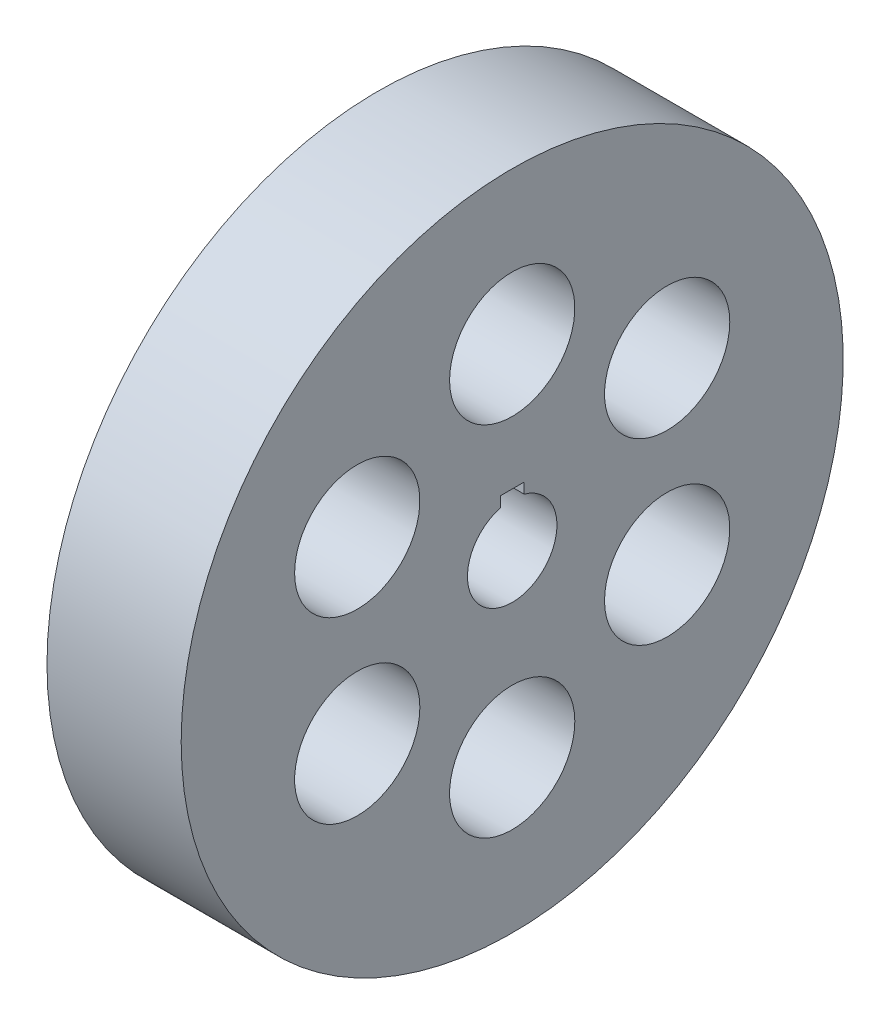
SolidWorks part; units mm, degrees
ref_plane "Front Plane" through (0, 0, 0) normal (0, 0, 1) x (1, 0, 0)
ref_plane "Top Plane" through (0, 0, 0) normal (0, 1, 0) x (1, 0, 0)
ref_plane "Right Plane" through (0, 0, 0) normal (1, 0, 0) x (0, 0, -1)
sketch "Sketch1" plane through (0, 0, 0) normal (0, 1, 0) x (1, 0, 0)
  line L0 (-137.76, 0) -> (199.68, 0) construction
  line L1 (0, 0) -> (0, 30)
  line L2 (0, 30) -> (35, 30)
  line L3 (35, 30) -> (35, 91)
  line L4 (30, 96) -> (25, 96)
  line L5 (25, 96) -> (25, 111)
  line L6 (25, 111) -> (70, 111)
  line L7 (70, 111) -> (70, 0)
  line L8 (0, 0) -> (70, 0)
  arc A0 (35, 91) -> (30, 96) centre (30, 91) ccw
  point P13 (35, 96)
  dimension "D7" = 5
  dimension "D1" = 30
  dimension "D2" = 111
  dimension "D3" = 96
  dimension "D4" = 70
  dimension "D5" = 45
  dimension "D6" = 35
revolve "Revolve1" add sketch "Sketch1" angle 360 about L0
sketch "Sketch2" plane through (0, 0, 0) normal (-1, 0, 0) x (0, 0, 1)
  line L0 (0, 46.7058) -> (0, -26.4489) construction
  line L1 (-4, 10.494) -> (-4, 17.494)
  line L2 (-4, 17.494) -> (4, 17.494)
  line L3 (4, 17.494) -> (4, 10.494)
  arc A0 (-4, 10.494) -> (4, 10.494) centre (0, 0) ccw
  dimension "D1" = 8
  dimension "D2" = 4
  dimension "D3" = 7
extrude "Cut-Extrude1" cut sketch "Sketch2" against normal through all
sketch "Sketch3" plane through (35, 0, 0) normal (-1, 0, 0) x (0, 0, 1)
  line L0 (0, 103.2431) -> (0, -120.3335) construction
  line L1 (-84.3315, 0) -> (83.7712, 0) construction
sketch "Sketch4" plane through (35, 0, 0) normal (-1, 0, 0) x (0, 0, 1)
  line L0 (0, 103.2431) -> (0, -120.3335) construction
  line L1 (0, 0) -> (191.3397, 110.47) construction
  line L2 (-84.3315, 0) -> (83.7712, 0) construction
  line L3 (0, 123.5797) -> (0, -84.2962) construction
  line L4 (-84.3315, 0) -> (104.0799, 0) construction
  circle A0 centre (0, 60) radius 21
  circle A1 centre (0, 0) radius 60 construction
  circle A2 centre (51.9615, 30) radius 21
  circle A3 centre (-51.9615, 30) radius 21
  circle A4 centre (51.9615, -30) radius 21
  circle A5 centre (0, -60) radius 21
  circle A6 centre (-51.9615, -30) radius 21
  dimension "D1" = 30
  dimension "D2" = 120
extrude "Cut-Extrude3" cut sketch "Sketch4" against normal through all
sketch "Sketch5" plane through (0, 0, 0) normal (-1, 0, 0) x (0, 0, 1)
  line L0 (4, 10.494) -> (4, 17.494) construction
  line L1 (-4, 17.494) -> (4, 17.494)
  line L2 (-4, 17.494) -> (-4, 13.994)
  line L3 (-4, 13.994) -> (4, 13.994)
  line L4 (4, 17.494) -> (4, 13.994)
extrude "Boss-Extrude1" add sketch "Sketch5" against normal blind 70
sketch "Sketch6" plane through (0, 0, 0) normal (-1, 0, 0) x (0, 0, 1)
  circle A1 centre (0, 0) radius 15
extrude "Cut-Extrude4" cut sketch "Sketch6" against normal through all
sketch "Sketch7" plane through (0, 0, 0) normal (-1, 0, 0) x (0, 0, 1)
  line L0 (0, 103.2431) -> (0, -120.3335) construction
  line L1 (-4, 11.5) -> (4, 11.5)
  line L2 (-4, 11.5) -> (-4, 18.5)
  line L3 (-4, 18.5) -> (4, 18.5)
  line L4 (4, 11.5) -> (4, 18.5)
  line L5 (-4, 11.5) -> (4, 18.5) construction
  line L6 (-4, 18.5) -> (4, 11.5) construction
  circle A0 centre (0, 0) radius 15 construction
  point P0 (0, 15)
  dimension "D1" = 7
  dimension "D2" = 8
extrude "Cut-Extrude5" cut sketch "Sketch7" against normal through all
sketch "Sketch8" plane through (0, 0, 0) normal (-1, 0, 0) x (0, 0, 1)
  line L2 (-4, 18.5) -> (4, 18.5)
  line L3 (-4, 18.5) -> (-4, 17.9568)
  line L4 (4, 18.5) -> (4, 17.9568)
  line L5 (-4, 17.9568) -> (4, 17.9568)
  dimension "D1" = 3.5
extrude "Boss-Extrude2" add sketch "Sketch8" against normal up to surface (70 mm away)
ref_plane "Plane5" through (0, 14.4568, 4) normal (0, 1, 0) x (1, 0, 0)
sketch "Sketch10" plane through (0, 0, 0) normal (-1, 0, 0) x (0, 0, 1)
  line L0 (-4, 17.9568) -> (-4, 14.4568)
